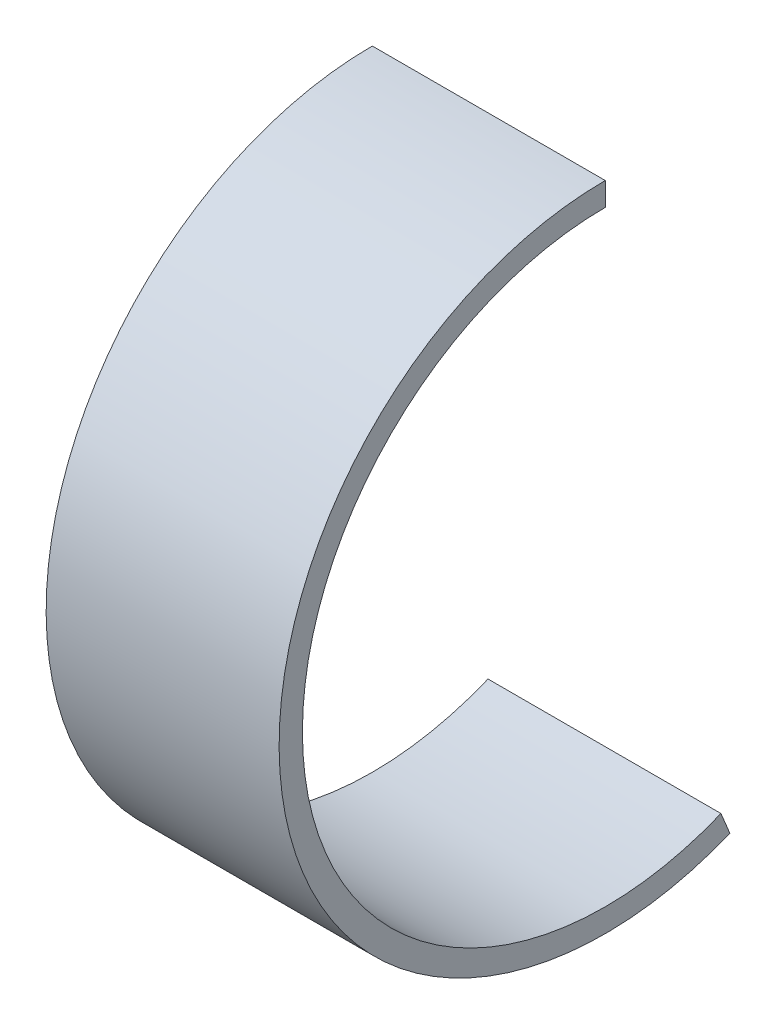
SolidWorks part; units mm, degrees
ref_plane "Front Plane" through (0, 0, 0) normal (0, 0, 1) x (1, 0, 0)
ref_plane "Top Plane" through (0, 0, 0) normal (0, 1, 0) x (1, 0, 0)
ref_plane "Right Plane" through (0, 0, 0) normal (1, 0, 0) x (0, 0, -1)
sketch "Sketch1" plane through (0, 0, 0) normal (1, 0, 0) x (0, 0, -1)
  arc A0 (0, 660.4) -> (252.28, -610.3138) centre (0, 0) ccw
extrude "Extrude-Thin1" add sketch "Sketch1" along normal blind 508 thin
